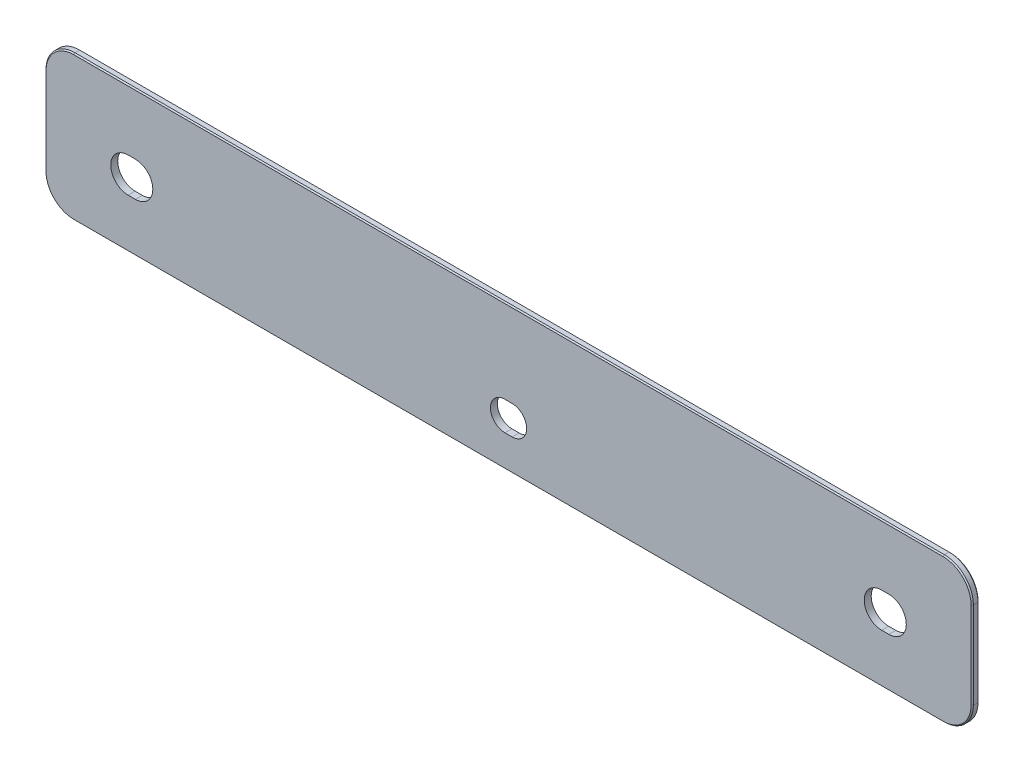
SolidWorks part; units mm, degrees
ref_plane "Front Plane" through (0, 0, 0) normal (1, 0, 0) x (0, 1, 0)
ref_plane "Top Plane" through (0, 0, 0) normal (0, 0, 1) x (0, 1, 0)
ref_plane "Right Plane" through (0, 0, 0) normal (0, 1, 0) x (-1, 0, 0)
sketch "Sketch1" plane through (0, 0, 0) normal (0, 0, 1) x (0, 1, 0)
  line L0 (0, 130) -> (0, -130) construction
  line L1 (0, 128.75) -> (0, 131.25) construction
  line L2 (-6, 128.75) -> (-6, 131.25)
  line L3 (6, 128.75) -> (6, 131.25)
  line L4 (0, -131.25) -> (0, -128.75) construction
  line L5 (-6, -131.25) -> (-6, -128.75)
  line L6 (6, -131.25) -> (6, -128.75)
  line L7 (2, 0) -> (0, 0) construction
  line L10 (-23, -160) -> (27, -160)
  line L11 (-23, -160) -> (-23, 160)
  line L12 (-23, 160) -> (27, 160)
  line L13 (27, -160) -> (27, 160)
  line L14 (-23, -160) -> (27, 160) construction
  line L15 (-23, 160) -> (27, -160) construction
  line L16 (-7, 0) -> (0, 0) construction
  line L17 (-7, 1.25) -> (-7, -1.25) construction
  line L18 (-2, 1.25) -> (-2, -1.25)
  line L19 (-12, 1.25) -> (-12, -1.25)
  arc A0 (-6, 128.75) -> (6, 128.75) centre (0, 128.75) ccw
  arc A1 (6, 131.25) -> (-6, 131.25) centre (0, 131.25) ccw
  arc A2 (-6, -131.25) -> (6, -131.25) centre (0, -131.25) ccw
  arc A3 (6, -128.75) -> (-6, -128.75) centre (0, -128.75) ccw
  arc A7 (-2, 1.25) -> (-12, 1.25) centre (-7, 1.25) ccw
  arc A8 (-12, -1.25) -> (-2, -1.25) centre (-7, -1.25) ccw
  point P7 (0, 130)
  point P13 (0, -130)
  point P20 (2, 0)
  point P31 (-7, 0)
  dimension "D3" = 6
  dimension "D5" = 5
  dimension "D1" = 260
  dimension "D2" = 2.5
  dimension "D4" = 7
  dimension "D6" = 27
  dimension "D7" = 23
  dimension "D8" = 320
extrude "Boss-Extrude1" add sketch "Sketch1" along normal blind 2.4
sketch "Sketch2" plane through (0, 0, 2.4) normal (0, 0, 1) x (1, 0, 0)
  line L0 (-160, 0) -> (-65, 0)
  line L1 (-160, 27) -> (-160, -23) construction
  line L2 (-65, 0) -> (-65, -7)
  line L3 (-65, -7) -> (65, -7)
  line L4 (65, -7) -> (65, 0)
  line L5 (65, 0) -> (160, 0)
  line L6 (160, -23) -> (160, 27) construction
  line L7 (128.75, 6) -> (128.75, -6)
  line L8 (0, 0) -> (0, -7)
  arc A1 (1.25, -12) -> (1.25, -2) centre (1.25, -7) ccw construction
  point P15 (6.25, -7)
  point P21 (-58.2434, 0)
  dimension "D1" = 130
fillet "Fillet1" radius 10 4 edges at (-160, -23, 1.2) (160, -23, 1.2) (160, 27, 1.2) (-160, 27, 1.2)
chamfer "Chamfer1" distance 0.4 angle 45 16 edges at (160, 2, 2.4) (157.0711, 24.0711, 2.4) (157.0711, -20.0711, 2.4) (0, 27, 2.4) (0, -23, 2.4) (-157.0711, 24.0711, 2.4) (-157.0711, -20.0711, 2.4) (-160, 2, 2.4) (160, 2, 0) (157.0711, 24.0711, 0) (157.0711, -20.0711, 0) (0, 27, 0) (0, -23, 0) (-157.0711, 24.0711, 0) (-157.0711, -20.0711, 0) (-160, 2, 0)
